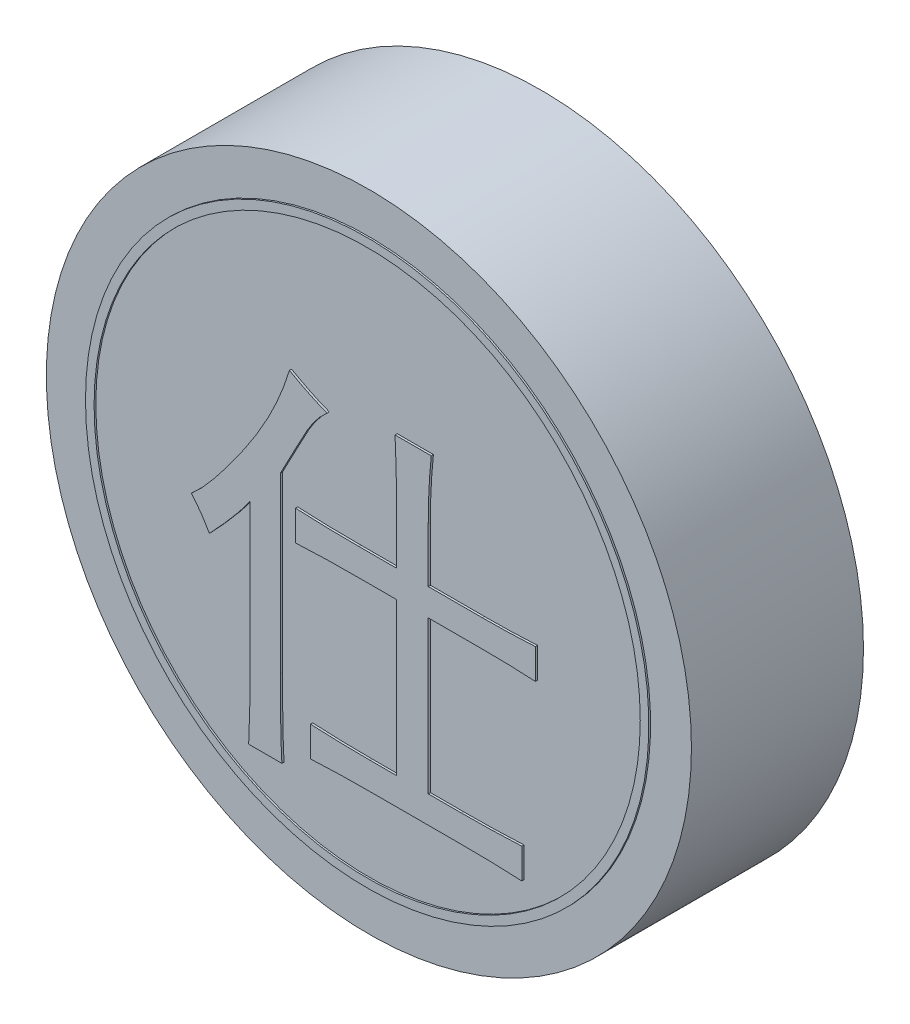
SolidWorks part; units mm, degrees
ref_plane "前视基准面" through (0, 0, 0) normal (0, 0, 1) x (1, 0, 0)
ref_plane "上视基准面" through (0, 0, 0) normal (0, 1, 0) x (1, 0, 0)
ref_plane "右视基准面" through (0, 0, 0) normal (1, 0, 0) x (0, 0, -1)
other "Configuration Table"
sketch "草图1" plane through (0, 0, 0) normal (0, 0, 1) x (1, 0, 0)
  circle A0 centre (0, 0) radius 15
  dimension "D1" = 30
extrude "Diameter30_Height8" add sketch "草图1" against normal blind 8
sketch "草图2" plane through (0, 0, 0) normal (0, 0, 1) x (1, 0, 0)
  text T0 "仕" font "SimHei" height 12
extrude "Character_仕" add sketch "草图2" along normal blind 0.1
sketch "草图3" plane through (0, 0, 0) normal (0, 0, 1) x (1, 0, 0)
  circle A0 centre (0, 0) radius 13.1
  circle A1 centre (0, 0) radius 12.7
extrude "Ink_ring" add sketch "草图3" along normal blind 0.08
